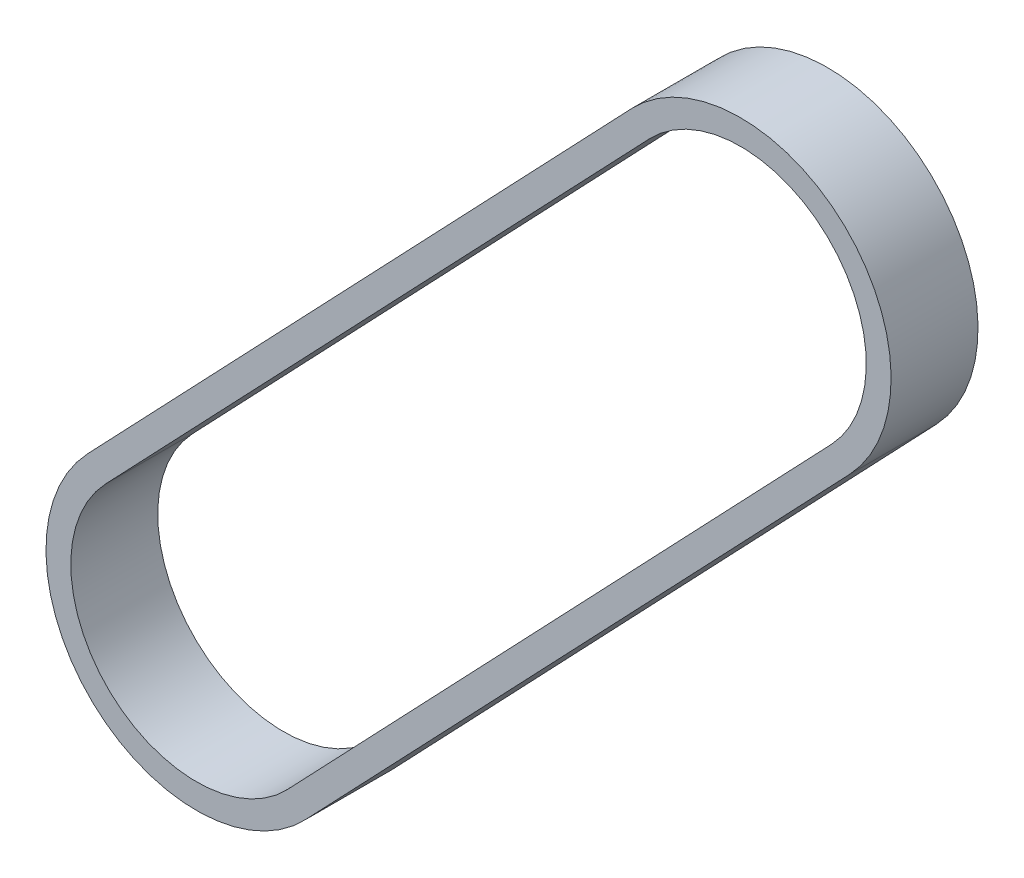
SolidWorks part; units mm, degrees
material "BUTYL"
ref_plane "前视基准面" through (0, 0, 0) normal (0, 0, 1) x (1, 0, 0)
ref_plane "上视基准面" through (0, 0, 0) normal (0, 1, 0) x (1, 0, 0)
ref_plane "右视基准面" through (0, 0, 0) normal (1, 0, 0) x (0, 0, -1)
sketch "草图2" plane through (0, 0, 0) normal (0, 0, 1) x (1, 0, 0)
  line L0 (0, 0) -> (1, 0) construction
  line L1 (0, 0) -> (0, 1) construction
  line L2 (17.3278, -6.9843) -> (-26.4749, -52.9579)
  line L3 (-41.1358, -38.9893) -> (2.6669, 6.9843)
  arc A0 (2.6669, 6.9843) -> (17.3278, -6.9843) centre (9.9974, 0) cw
  arc A1 (-26.4749, -52.9579) -> (-41.1358, -38.9893) centre (-33.8053, -45.9736) cw
extrude "拉伸-薄壁1" add sketch "草图2" along normal blind 7 thin thin type one direction wall 2
